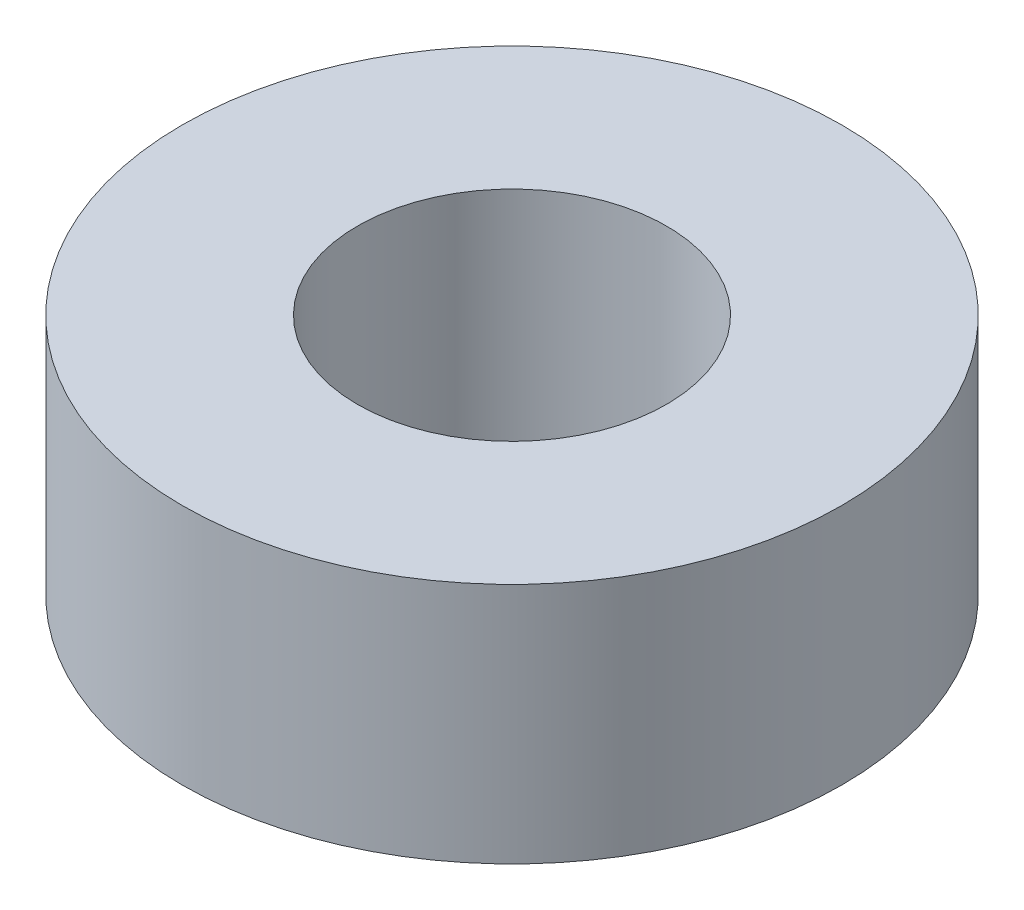
SolidWorks part; units mm, degrees
ref_plane "Front Plane" through (0, 0, 0) normal (0, 0, 1) x (1, 0, 0)
ref_plane "Top Plane" through (0, 0, 0) normal (0, 1, 0) x (1, 0, 0)
ref_plane "Right Plane" through (0, 0, 0) normal (1, 0, 0) x (0, 0, -1)
sketch "Sketch1" plane through (0, 0, 0) normal (0, 1, 0) x (1, 0, 0)
  circle A0 centre (0, 0) radius 3.2
  circle A1 centre (0, 0) radius 1.5
  dimension "D1" = 6.4
  dimension "D2" = 3
extrude "Boss-Extrude1" add sketch "Sketch1" along normal blind 2.35
